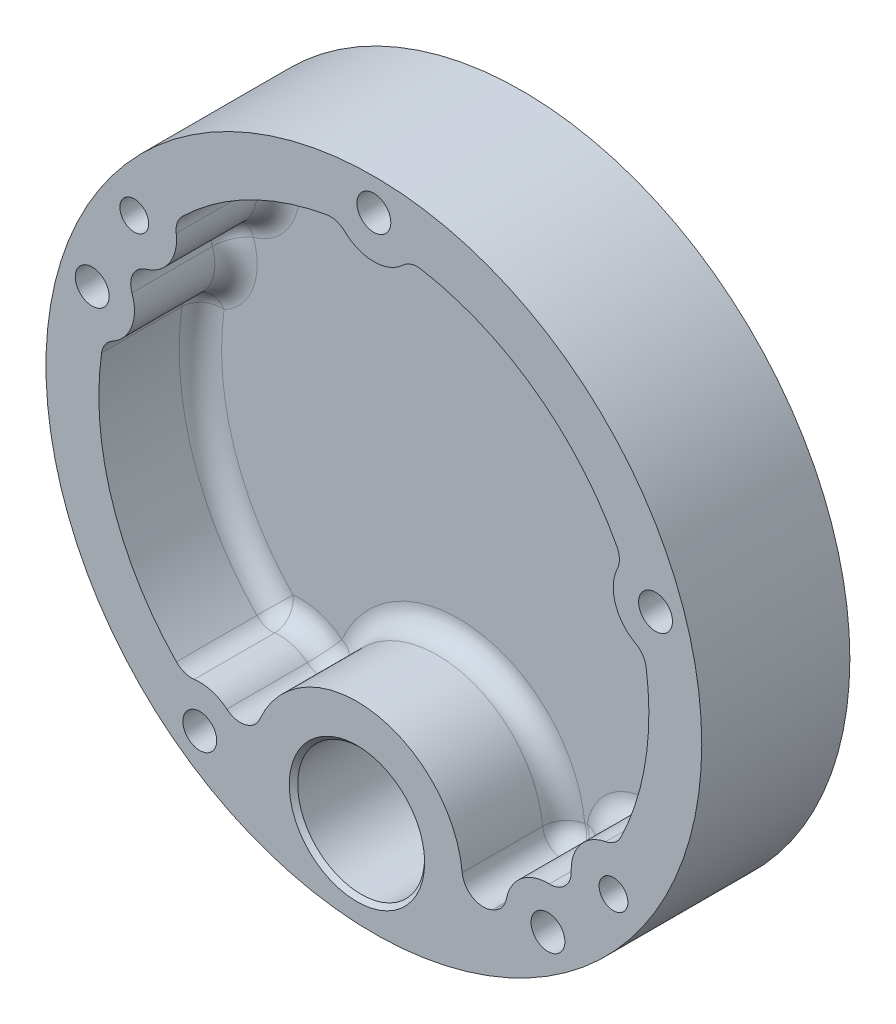
SolidWorks part; units mm, degrees
ref_plane "前视基准面" through (0, 0, 0) normal (0, 0, 1) x (1, 0, 0)
ref_plane "上视基准面" through (0, 0, 0) normal (0, 1, 0) x (1, 0, 0)
ref_plane "右视基准面" through (0, 0, 0) normal (1, 0, 0) x (0, 0, -1)
sketch "草图1" plane through (0, 0, 0) normal (0, 0, 1) x (1, 0, 0)
  circle A0 centre (0, 0) radius 77.5
  dimension "D1" = 155
extrude "凸台-拉伸1" add sketch "草图1" along normal blind 35
sketch "草图2" plane through (0, 0, 35) normal (0, 0, 1) x (1, 0, 0)
  line L1 (0, -19.25) -> (0, 19.25) construction
  line L2 (19.25, 0) -> (-19.25, 0) construction
  circle A0 centre (-4, -57) radius 15
  point P2 (-6.1089, -56.6532)
  dimension "D1" = 30
  dimension "D3" = 57
  dimension "D2" = 4
extrude "切除-拉伸1" cut sketch "草图2" against normal through all
chamfer "倒角1" distance 1 angle 45 2 edges at (11, -57, 35) (11, -57, 0)
sketch "草图3" plane through (0, 0, 0) normal (0, 0, 1) x (1, 0, 0)
  circle A0 centre (0, 0) radius 70 construction
  point P3 (0, 70)
  dimension "D1" = 140
hole_wizard "孔1" positions "草图3" profile "草图4" legacy end condition through all
sketch "草图4" plane through (0, 70, 0) normal (1, 0, 0) x (0, 1, 0)
  line L0 (0, 0) -> (0, 35)
  line L1 (0, 35) -> (4, 35)
  line L2 (4, 35) -> (4, 9)
  line L3 (4, 9) -> (7, 9)
  line L4 (7, 9) -> (7, 0)
  line L5 (7, 0) -> (0, 0)
  line L6 (0, 110) -> (0, -10) construction
  dimension "直径" = 8
  dimension "深度" = 35
  dimension "柱坑直径" = 14
  dimension "柱坑深度" = 9
pattern_circular "阵列(圆周)1" count 5 over 360 about axis through (0, 0, 0) along (0, 0, 1) of "孔1"
sketch "草图5" plane through (0, 0, 35) normal (0, 0, 1) x (1, 0, 0)
  line L0 (56.6312, -41.145) -> (-56.6312, 41.145) construction
  line L1 (19.25, 0) -> (-19.25, 0) construction
  circle A0 centre (0, 0) radius 70 construction
  point P3 (56.6312, -41.145)
  point P9 (-56.6312, 41.145)
  dimension "D1" = 140
  dimension "D2" = 36
hole_wizard "M8 螺纹孔1" positions "草图5" profile "草图6" tap size "M8" standard "GB" end condition through all
sketch "草图6" plane through (-56.6312, 41.145, 35) normal (1, 0, 0) x (0, -1, 0)
  line L0 (0, 0) -> (0, 35)
  line L1 (0, 35) -> (3.4, 35)
  line L2 (3.4, 35) -> (3.4, 0)
  line L5 (3.4, 0) -> (0, 0)
  line L11 (0, -6.35) -> (0, 107.95) construction
  dimension "通孔螺纹孔钻头直径" = 6.8
  dimension "通孔螺纹孔钻头深度" = 35
cosmetic thread "孔螺纹线1" parameters "D2"=8
cosmetic thread "孔螺纹线2" parameters "D2"=8
sketch "草图7" plane through (0, 0, 35) normal (0, 0, 1) x (1, 0, 0)
  arc A0 (57.4465, 30.4122) -> (11.1718, 64.0327) centre (0, 0) ccw
  arc A1 (20.8861, -54.6163) -> (-26.9519, -47.0899) centre (-4, -57) ccw
  arc A2 (-34.7432, -48.9489) -> (-42.4385, -46.7152) centre (-41.145, -56.6312) ccw
  arc A3 (-61.7919, 12.8487) -> (-57.1704, 25.0331) centre (-66.574, 21.6312) ccw
  arc A4 (-53.8561, 31.5377) -> (-46.7152, 42.4385) centre (-56.6312, 41.145) ccw
  arc A5 (-6.8749, 62.7381) -> (6.8749, 62.7381) centre (0, 70) ccw
  arc A6 (57.543, 25.9256) -> (61.7919, 12.8487) centre (66.574, 21.6312) ccw
  arc A7 (54.7972, -31.3146) -> (46.6366, -41.4745) centre (56.6312, -41.145) ccw
  arc A8 (41.4745, -46.6366) -> (31.3146, -54.7972) centre (41.145, -56.6312) ccw
  arc A9 (-11.1718, 64.0327) -> (-45.237, 46.6757) centre (0, 0) ccw
  arc A11 (-64.351, 9.1622) -> (-46.6757, -45.237) centre (0, 0) ccw
  arc A13 (28.0186, -58.6512) -> (28.5993, -58.3702) centre (0, 0) ccw
  arc A15 (58.3702, -28.5993) -> (64.351, 9.1622) centre (0, 0) ccw
  arc A16 (-34.7432, -48.9489) -> (-26.9519, -47.0899) centre (-31.5423, -45.1078) ccw
  arc A17 (20.8861, -54.6163) -> (28.0186, -58.6512) centre (25.8633, -54.1395) ccw
  arc A18 (57.543, 25.9256) -> (57.4465, 30.4122) centre (53.0275, 28.0728) ccw
  arc A19 (-6.8749, 62.7381) -> (-11.1718, 64.0327) centre (-10.3124, 59.1071) ccw
  arc A20 (-61.7919, 12.8487) -> (-64.351, 9.1622) centre (-59.4009, 8.4574) ccw
  arc A21 (54.7972, -31.3146) -> (58.3702, -28.5993) centre (53.8802, -26.3994) ccw
  arc A22 (31.3146, -54.7972) -> (28.5993, -58.3702) centre (26.3994, -53.8802) cw
  arc A23 (61.7919, 12.8487) -> (64.351, 9.1622) centre (59.4009, 8.4574) cw
  arc A24 (6.8749, 62.7381) -> (11.1718, 64.0327) centre (10.3124, 59.1071) cw
  arc A25 (-46.7152, 42.4385) -> (-45.237, 46.6757) centre (-41.7572, 43.0852) cw
  arc A26 (-42.4385, -46.7152) -> (-46.6757, -45.237) centre (-43.0852, -41.7572) cw
  arc A27 (-53.8561, 31.5377) -> (-57.1704, 25.0331) centre (-52.4686, 26.7341) ccw
  arc A28 (41.4745, -46.6366) -> (46.6366, -41.4745) centre (41.6393, -41.6393) ccw
  point P37 (20.5614, -61.6622)
  point P42 (-8.328, 64.4643)
  point P45 (-63.8827, 12.0001)
  point P48 (57.0478, -31.1536)
  point P51 (31.1536, -57.0478)
  point P58 (-47.2576, 44.6287)
  point P61 (-44.6287, -47.2576)
  dimension "D1" = 130
  dimension "D2" = 50
  dimension "D3" = 20
  dimension "D4" = 20
  dimension "D5" = 20
  dimension "D6" = 20
  dimension "D7" = 20
  dimension "D8" = 20
  dimension "D9" = 20
  dimension "D10" = 10
  dimension "D11" = 5
  dimension "D12" = 10
  dimension "D13" = 10
extrude "切除-拉伸2" cut sketch "草图7" against normal blind 24
fillet "圆角1" radius 5 26 edges at (-0.1145, -32.3038, 11) (-30.3818, -49.9713, 11) (-38.3573, -47.0276, 11) (-44.7322, -46.4782, 11) (-61.8187, -20.0861, 11) (-63.5083, 11.3087, 11) (-57.2239, 18.0847, 11) (-56.9237, 29.0041, 11) (-48.2663, 35.6652, 11) (-46.4782, 44.7322, 11) (-29.5094, 57.9154, 11) (-8.8699, 63.8946, 11) (0, 60, 11) (8.8699, 63.8946, 11) (38.206, 52.5861, 11) (58.0264, 28.1803, 11) (57.0634, 18.541, 11) (63.5083, 11.3087, 11) (64.1997, -10.1682, 11) (56.9054, -30.3803, 11) (48.8347, -34.8828, 11) (45.1749, -45.1749, 11) (34.8828, -48.8347, 11) (30.3803, -56.9054, 11) (28.3093, -58.5114, 11) (23.4014, -58.4914, 11)
